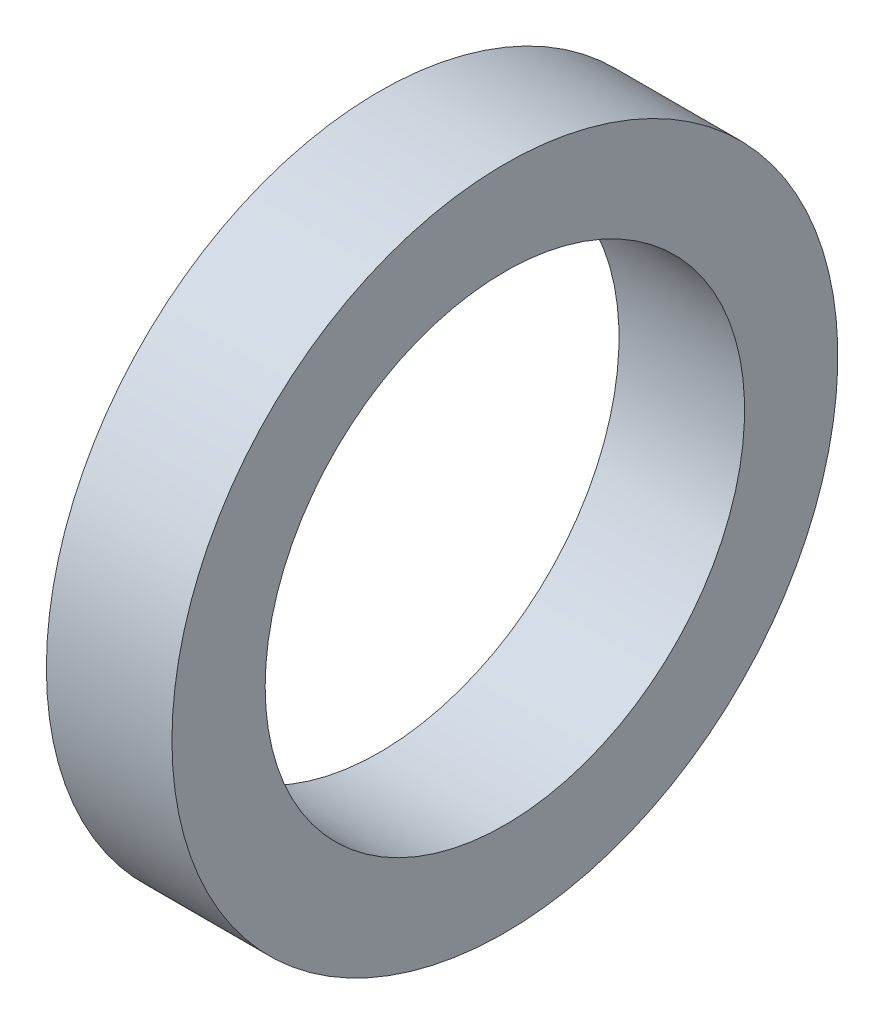
SolidWorks part; units mm, degrees
ref_plane "Front Plane" through (0, 0, 0) normal (0, 0, 1) x (1, 0, 0)
ref_plane "Top Plane" through (0, 0, 0) normal (0, 1, 0) x (1, 0, 0)
ref_plane "Right Plane" through (0, 0, 0) normal (1, 0, 0) x (0, 0, -1)
sketch "Sketch1" plane through (0, 0, 0) normal (0, 1, 0) x (1, 0, 0)
  line L0 (0, 0) -> (17.6667, 0) construction
  line L2 (0, 9) -> (4.7143, 9)
  line L3 (0, 9) -> (0, 12.5)
  line L4 (0, 12.5) -> (4.7143, 12.5)
  line L5 (4.7143, 9) -> (4.7143, 12.5)
  dimension "D1" = 18
  dimension "D2" = 25
revolve "Revolve1" add sketch "Sketch1" angle 360 about L0
